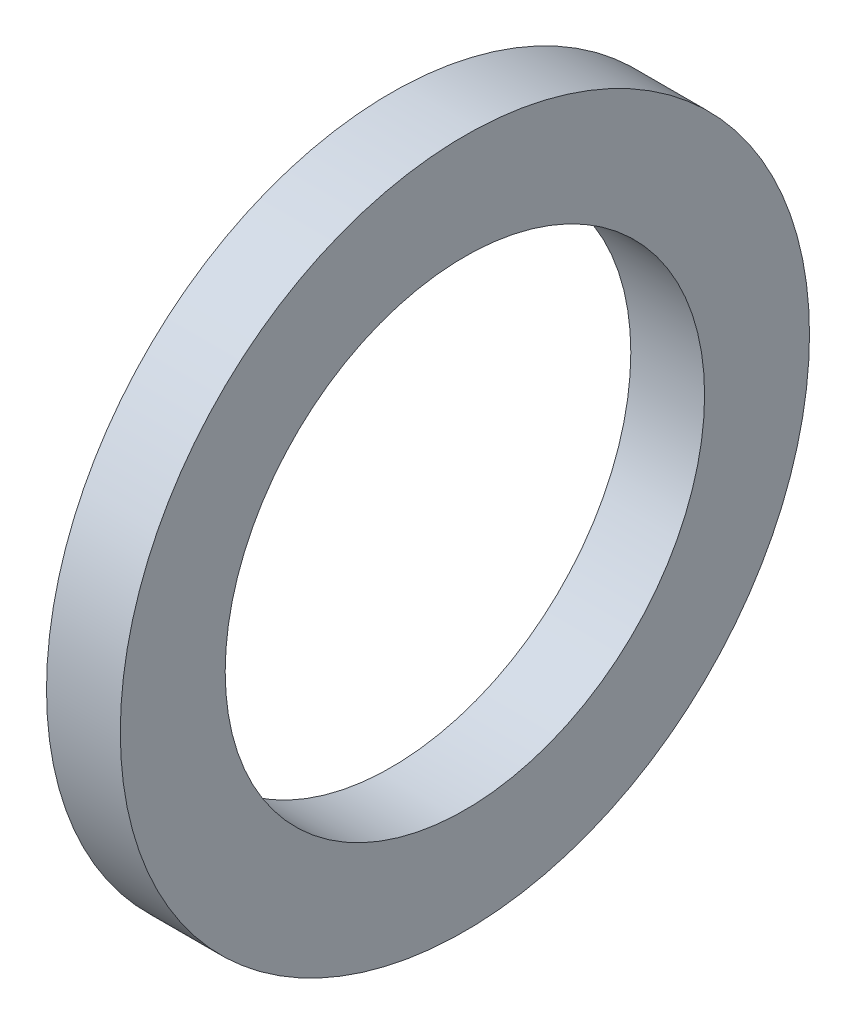
SolidWorks part; units mm, degrees
material "1.4003 (X2CrNi12)"
ref_plane "Ön Düzlem" through (0, 0, 0) normal (0, 0, 1) x (1, 0, 0)
ref_plane "Üst Düzlem" through (0, 0, 0) normal (0, 1, 0) x (1, 0, 0)
ref_plane "Sağ Düzlem" through (0, 0, 0) normal (1, 0, 0) x (0, 0, -1)
sketch "Çizim2" plane through (0, 0, 0) normal (0, 1, 0) x (1, 0, 0)
  line L0 (0, 0) -> (4.1201, 0) construction
  line L1 (0, 19.2425) -> (0, 13.3852)
  line L2 (0, 13.3852) -> (4.1201, 13.3852)
  line L3 (4.1201, 13.3852) -> (4.1201, 19.2425)
  line L4 (4.1201, 19.2425) -> (0, 19.2425)
revolve "Döndür1" add sketch "Çizim2" angle 360 about L0
